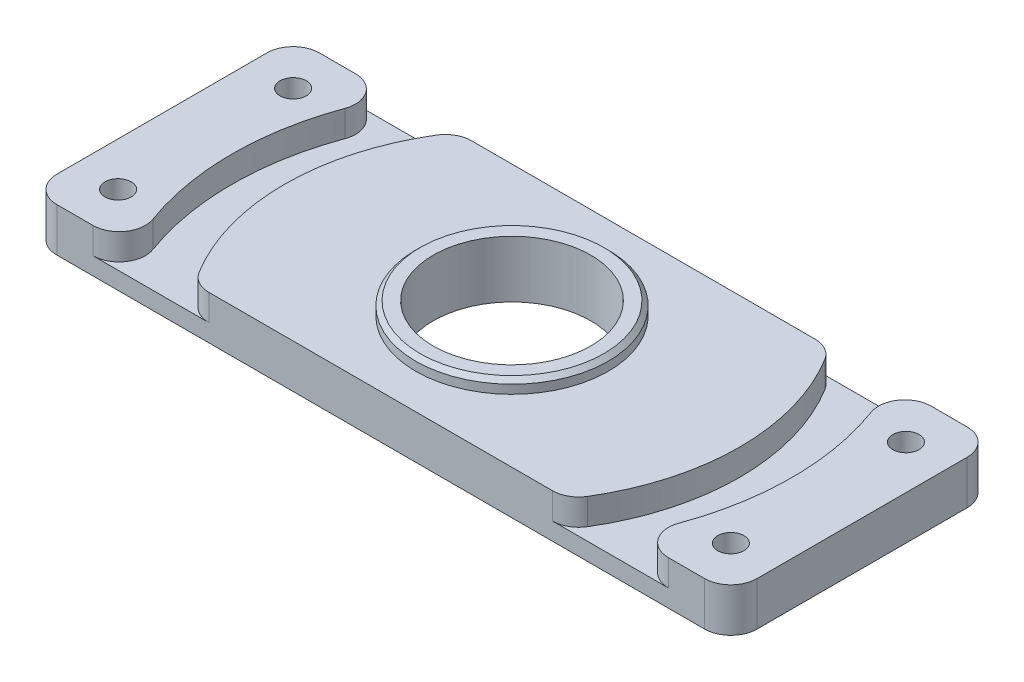
SolidWorks part; units mm, degrees
ref_plane "前视基准面" through (0, 0, 0) normal (0, 0, 1) x (1, 0, 0)
ref_plane "上视基准面" through (0, 0, 0) normal (0, 1, 0) x (1, 0, 0)
ref_plane "右视基准面" through (0, 0, 0) normal (1, 0, 0) x (0, 0, -1)
other "Configuration Table"
sketch "草图1" plane through (0, 0, 0) normal (0, 1, 0) x (1, 0, 0)
  line L1 (-40, 15) -> (40, 15)
  line L2 (-40, 15) -> (-40, -15)
  line L3 (-40, -15) -> (40, -15)
  line L4 (40, 15) -> (40, -15)
  line L5 (-40, 15) -> (40, -15) construction
  line L6 (-40, -15) -> (40, 15) construction
  circle A0 centre (0, 0) radius 9
  circle A1 centre (0, 0) radius 11 construction
  dimension "D1" = 18
  dimension "D2" = 22
  dimension "D3" = 30
  dimension "D4" = 80
extrude "凸台-拉伸1" add sketch "草图1" against normal blind 5
sketch "草图4" plane through (0, 0, 0) normal (0, 1, 0) x (1, 0, 0)
  circle A0 centre (0, 0) radius 9 construction
  circle A1 centre (0, 0) radius 9
  circle A2 centre (0, 0) radius 11 construction
  circle A3 centre (0, 0) radius 11
extrude "凸台-拉伸4" add sketch "草图4" along normal blind 1.5
sketch "草图5" plane through (0, 0, 0) normal (0, 1, 0) x (1, 0, 0)
  circle A0 centre (0, 0) radius 29 construction
  circle A1 centre (0, 0) radius 26
  circle A2 centre (0, 0) radius 32
  dimension "D1" = 58
  dimension "D2" = 6
  dimension "D3" = 3
extrude "切除-拉伸1" cut sketch "草图5" against normal blind 3
sketch "草图8" plane through (0, -5, 0) normal (0, -1, 0) x (1, 0, 0)
  line L0 (0, 0) -> (0, 15) construction
  line L2 (35, 10) -> (35, -10) construction
  line L3 (0, 0) -> (35, 0) construction
  line L4 (-40, 15) -> (40, 15) construction
  circle A0 centre (35, 10) radius 1.5
  circle A1 centre (35, -10) radius 1.5
  circle A2 centre (-35, -10) radius 1.5
  circle A3 centre (-35, 10) radius 1.5
  dimension "D1" = 3
  dimension "D2" = 20
  dimension "D3" = 35
extrude "切除-拉伸2" cut sketch "草图8" against normal blind 10
fillet "圆角1" radius 3 12 edges at (40, -2.5, -15) (-40, -2.5, -15) (40, -2.5, 15) (-40, -2.5, 15) (-28.2666, -1.5, -15) (28.2666, -1.5, -15) (28.2666, -1.5, 15) (-28.2666, -1.5, 15) (-21.2368, -1.5, -15) (21.2368, -1.5, -15) (21.2368, -1.5, 15) (-21.2368, -1.5, 15)
chamfer "倒角1" distance 0.5 angle 45 1 edges at (0, 1.5, 11)
